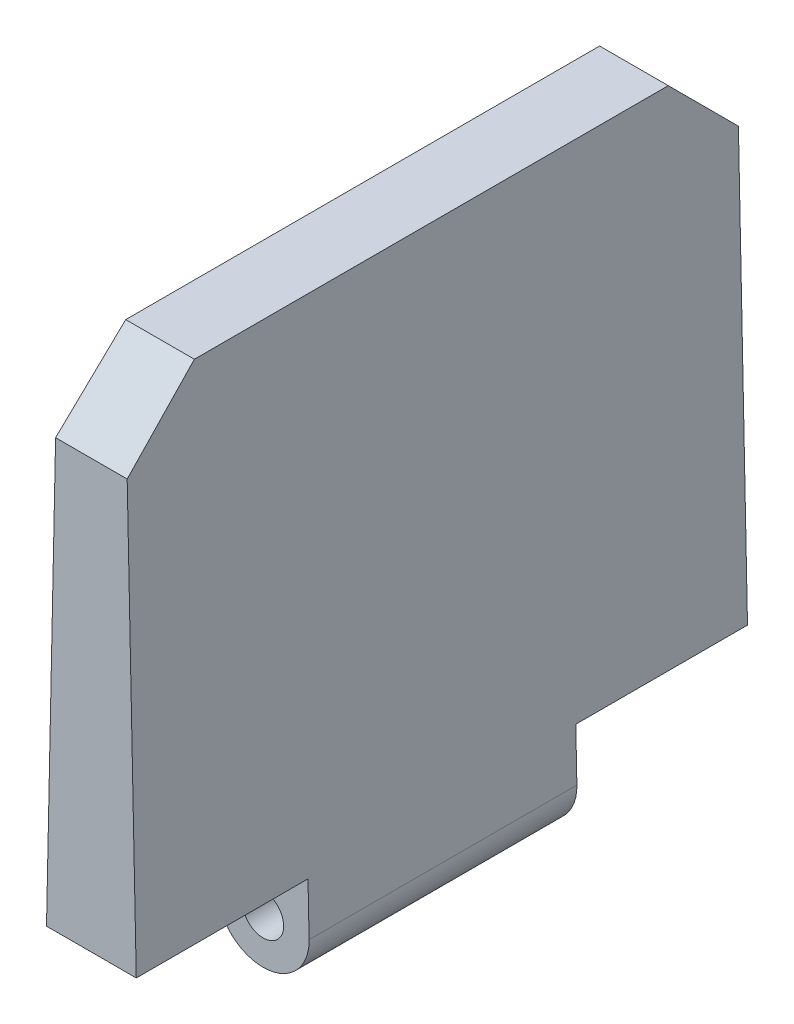
SolidWorks part; units mm, degrees
ref_plane "Front Plane" through (0, 0, 0) normal (0, 0, 1) x (1, 0, 0)
ref_plane "Top Plane" through (0, 0, 0) normal (0, 1, 0) x (1, 0, 0)
ref_plane "Right Plane" through (0, 0, 0) normal (1, 0, 0) x (0, 0, -1)
sketch "Sketch1" plane through (0, 0, 0) normal (0, 0, 1) x (1, 0, 0)
  line L0 (-1.27, 20.32) -> (-1.7014, 0.0362)
  line L1 (1.7014, 0.0362) -> (1.27, 20.32)
  line L2 (1.27, 20.32) -> (-1.27, 20.32)
  line L3 (0, 0) -> (0, 20.32) construction
  arc A0 (-1.7014, 0.0362) -> (1.7014, 0.0362) centre (0, 0) ccw
  dimension "D1" = 1.7018
  dimension "D2" = 20.32
  dimension "D3" = 2.54
extrude "Extrude1" add sketch "Sketch1" against normal blind 22.61
chamfer "Chamfer1" distance 2.54 angle 45 2 edges at (0, 20.32, -22.61) (0, 20.32, 0)
sketch "Sketch2" plane through (0, 0, 0) normal (0, 0, 1) x (1, 0, 0)
  circle A0 centre (0, 0) radius 0.76
  dimension "D1" = 1.52
extrude "Cut-Extrude1" cut sketch "Sketch2" against normal through all
sketch "Sketch3" plane through (0, 0, 0) normal (1, 0, 0) x (0, 0, -1)
  line L0 (0, -1.7018) -> (22.61, -1.7018) construction
  line L1 (6.352, -1.7018) -> (0, -1.7018)
  line L2 (6.352, -1.7018) -> (6.352, 1.9631)
  line L3 (6.352, 1.9631) -> (0, 1.9631)
  line L4 (0, -1.7018) -> (0, 1.9631)
  line L5 (0, 0.0362) -> (0, 17.78) construction
  line L6 (22.61, 0.0362) -> (22.61, 17.78) construction
  line L7 (16.258, -1.7018) -> (22.61, -1.7018)
  line L8 (16.258, -1.7018) -> (16.258, 1.9631)
  line L9 (16.258, 1.9631) -> (22.61, 1.9631)
  line L10 (22.61, -1.7018) -> (22.61, 1.9631)
  line L11 (11.305, 20.32) -> (11.305, -1.7018) construction
  line L12 (20.07, 20.32) -> (2.54, 20.32) construction
  dimension "D1" = 9.906
  dimension "D2" = 3.6649
extrude "Extrude2" cut sketch "Sketch3" against normal through all and the other way through all
